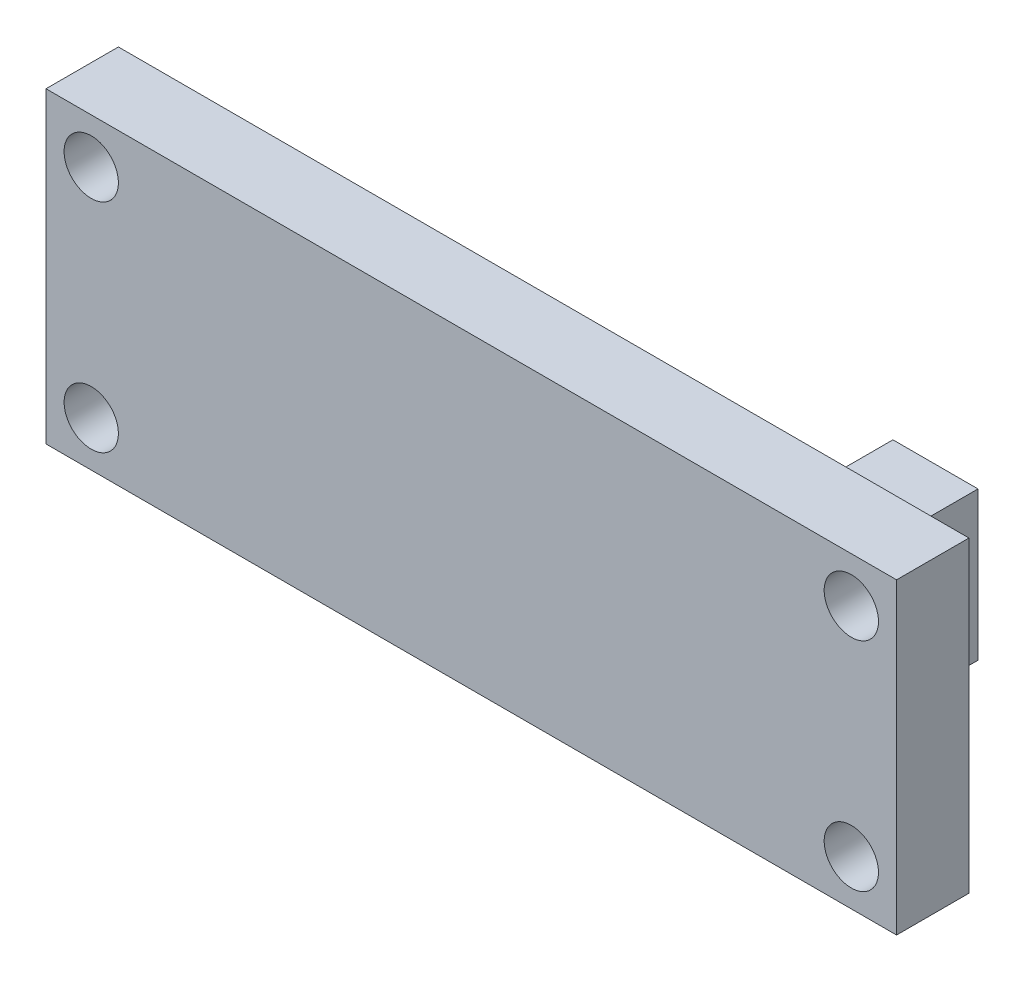
SolidWorks part; units mm, degrees
material "Fibra de vidrio-E"
ref_plane "Alzado" through (0, 0, 0) normal (0, 0, 1) x (1, 0, 0)
ref_plane "Planta" through (0, 0, 0) normal (0, 1, 0) x (1, 0, 0)
ref_plane "Vista lateral" through (0, 0, 0) normal (1, 0, 0) x (0, 0, -1)
sketch "Croquis1" plane through (0, 0, 0) normal (0, 0, 1) x (1, 0, 0)
  line L1 (-47, 17) -> (0, 17)
  line L2 (-47, 17) -> (-47, 0)
  line L3 (-47, 0) -> (0, 0)
  line L4 (0, 17) -> (0, 0)
  dimension "D1" = 17
  dimension "D2" = 47
  dimension "D3" = 0
  dimension "D4" = 0
extrude "Saliente-Extruir1" add sketch "Croquis1" along normal blind 4
sketch "Croquis2" plane through (0, 0, 4) normal (0, 0, 1) x (1, 0, 0)
  line L0 (0, 0) -> (0, 17) construction
  line L1 (0, 17) -> (-47, 17) construction
  line L2 (-47, 0) -> (0, 0) construction
  line L3 (-47, 17) -> (-47, 0) construction
  line L4 (-44.5, 14.5) -> (-2.5, 14.5) construction
  line L5 (-44.5, 14.5) -> (-44.5, 2.5) construction
  circle A0 centre (-2.5, 14.5) radius 1.5
  circle A1 centre (-2.5, 2.5) radius 1.5
  circle A2 centre (-44.5, 14.5) radius 1.5
  circle A3 centre (-44.5, 2.5) radius 1.5
  dimension "D1" = 3
  dimension "D2" = 3
  dimension "D3" = 3
  dimension "D4" = 3
  dimension "D5" = 2.5
  dimension "D6" = 2.5
  dimension "D7" = 2.5
  dimension "D8" = 2.5
  dimension "D9" = 2.5
  dimension "D10" = 2.5
  dimension "D11" = 2.5
  dimension "D12" = 2.5
extrude "Cortar-Extruir1" cut sketch "Croquis2" against normal through all
sketch "Croquis3" plane through (0, 0, 0) normal (0, 0, -1) x (-1, 0, 0)
  line L0 (0, 0) -> (0, 17) construction
  line L1 (6.5, 12.6) -> (11.2, 12.6)
  line L2 (6.5, 12.6) -> (6.5, 4.4)
  line L3 (6.5, 4.4) -> (11.2, 4.4)
  line L4 (11.2, 12.6) -> (11.2, 4.4)
  line L7 (0, 8.5) -> (47, 8.5) construction
  line L8 (47, 17) -> (47, 0) construction
  dimension "D1" = 4.7
  dimension "D2" = 8.2
  dimension "D3" = 4.1
  dimension "D4" = 6.5
extrude "Saliente-Extruir2" add sketch "Croquis3" along normal blind 7
